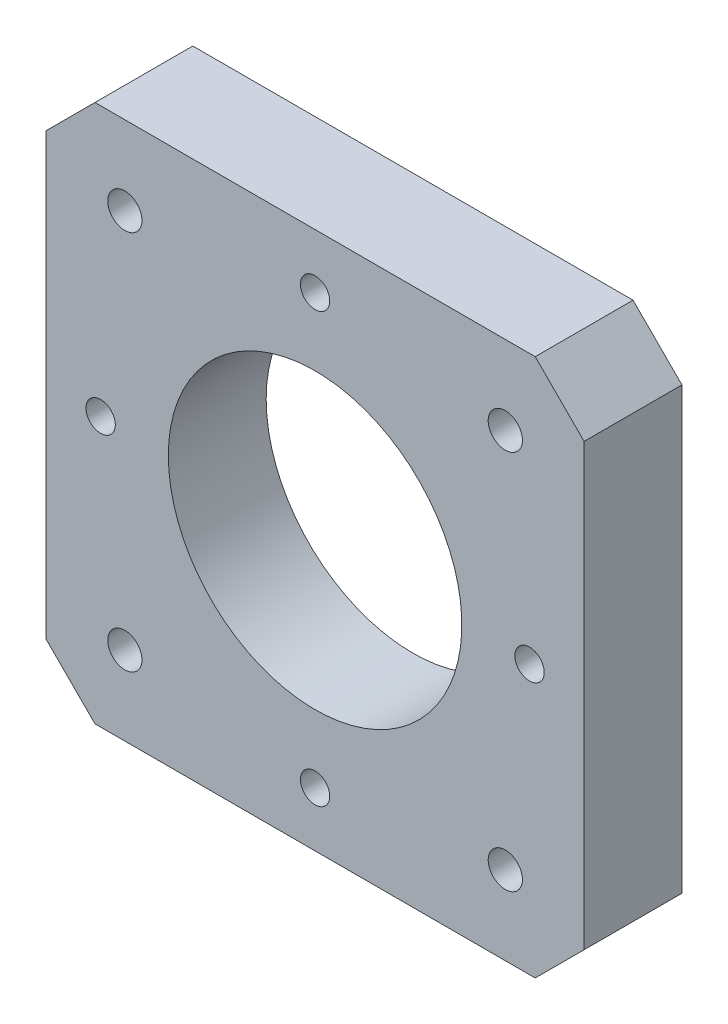
SolidWorks part; units mm, degrees
ref_plane "Front Plane" through (0, 0, 0) normal (0, 0, 1) x (1, 0, 0)
ref_plane "Top Plane" through (0, 0, 0) normal (0, 1, 0) x (1, 0, 0)
ref_plane "Right Plane" through (0, 0, 0) normal (1, 0, 0) x (0, 0, -1)
sketch "Sketch1" plane through (0, 0, 0) normal (0, 0, 1) x (1, 0, 0)
  line L1 (-27.5, 27.5) -> (27.5, 27.5)
  line L2 (-27.5, 27.5) -> (-27.5, -27.5)
  line L3 (-27.5, -27.5) -> (27.5, -27.5)
  line L4 (27.5, 27.5) -> (27.5, -27.5)
  line L5 (-27.5, 27.5) -> (27.5, -27.5) construction
  line L6 (-27.5, -27.5) -> (27.5, 27.5) construction
  circle A0 centre (0, 0) radius 27.5 construction
  circle A1 centre (19.4454, 19.4454) radius 1.75
  circle A2 centre (-19.4454, 19.4454) radius 1.75
  circle A3 centre (-19.4454, -19.4454) radius 1.75
  circle A4 centre (19.4454, -19.4454) radius 1.75
  point P0 (0, 0)
  dimension "D1" = 55
  dimension "D2" = 3.5
extrude "Boss-Extrude1" add sketch "Sketch1" along normal blind 10
sketch "Sketch2" plane through (0, 0, 0) normal (0, 0, -1) x (-1, 0, 0)
  circle A0 centre (0, 0) radius 15
  dimension "D1" = 30
extrude "Cut-Extrude1" cut sketch "Sketch2" against normal through all
sketch "Sketch3" plane through (0, 0, 0) normal (0, 0, -1) x (-1, 0, 0)
  line L0 (0, 29.6985) -> (-29.6985, 0) construction
  line L1 (0, 29.6985) -> (29.6985, 0) construction
  line L2 (-29.6985, 0) -> (0, -29.6985) construction
  line L3 (29.6985, 0) -> (0, -29.6985) construction
  line L4 (0, 29.6985) -> (0, -29.6985) construction
  line L5 (-29.6985, 0) -> (29.6985, 0) construction
  line L6 (0, 21.9203) -> (-21.9203, 0) construction
  line L7 (0, 21.9203) -> (21.9203, 0) construction
  line L8 (-21.9203, 0) -> (0, -21.9203) construction
  line L9 (21.9203, 0) -> (0, -21.9203) construction
  line L10 (0, 21.9203) -> (0, -21.9203) construction
  line L11 (-21.9203, 0) -> (21.9203, 0) construction
  circle A0 centre (0, 21.9203) radius 1.5
  circle A1 centre (21.9203, 0) radius 1.5
  circle A2 centre (0, -21.9203) radius 1.5
  circle A3 centre (-21.9203, 0) radius 1.5
  point P1 (0, 0)
  point P2 (0, 0)
  dimension "D3" = 3
  dimension "D1" = 42
  dimension "D2" = 31
extrude "Cut-Extrude2" cut sketch "Sketch3" against normal through all contours A0 | A3 | A2 | A1
sketch "Sketch4" plane through (0, 0, 0) normal (0, 0, -1) x (-1, 0, 0)
  circle A3 centre (0, 21.9203) radius 3.25
  circle A4 centre (21.9203, 0) radius 3.25
  circle A5 centre (0, -21.9203) radius 3.25
  circle A6 centre (-21.9203, 0) radius 3.25
  dimension "D1" = 6.5
  dimension "D2" = 6.5
  dimension "D3" = 6.5
  dimension "D4" = 6.5
extrude "Cut-Extrude3" cut sketch "Sketch4" against normal blind 6
chamfer "Chamfer1" distance 5 angle 45 4 edges at (-27.5, -27.5, 5) (27.5, -27.5, 5) (-27.5, 27.5, 5) (27.5, 27.5, 5)
